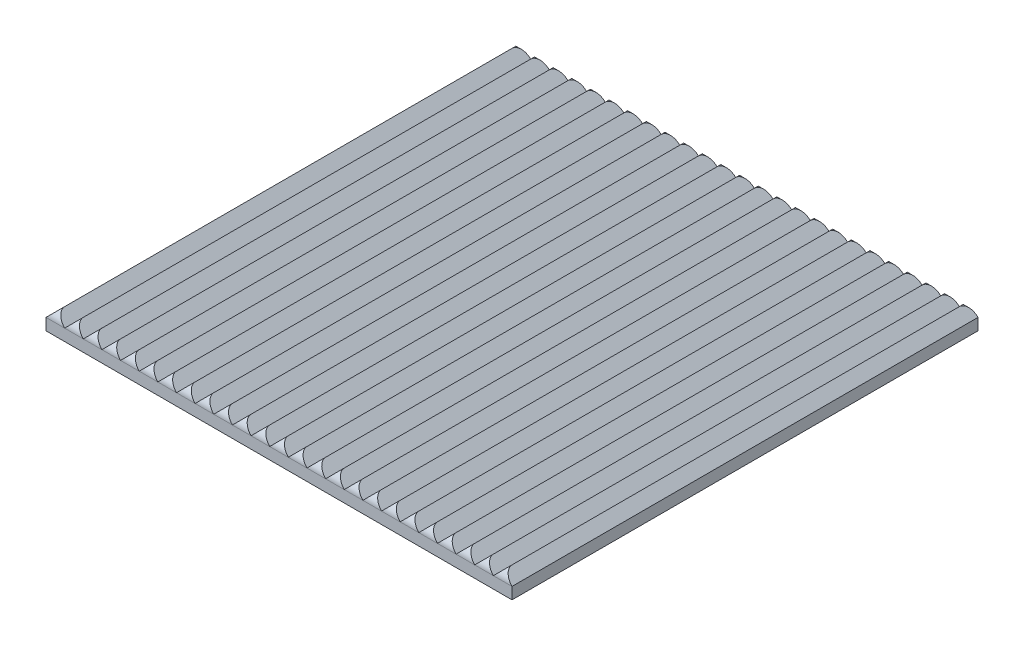
SolidWorks part; units mm, degrees
ref_plane "Front Plane" through (0, 0, 0) normal (0, 0, 1) x (1, 0, 0)
ref_plane "Top Plane" through (0, 0, 0) normal (0, 1, 0) x (1, 0, 0)
ref_plane "Right Plane" through (0, 0, 0) normal (1, 0, 0) x (0, 0, -1)
sketch "Sketch1" plane through (0, 0, 0) normal (0, 1, 0) x (1, 0, 0)
  line L0 (-27.5, 27.5) -> (27.5, 27.5)
  line L1 (-30, -30) -> (30, -30)
  line L2 (-30, -30) -> (-30, 30)
  line L3 (-30, 30) -> (30, 30)
  line L4 (30, -30) -> (30, 30)
  line L5 (-30, -30) -> (30, 30) construction
  line L6 (-30, 30) -> (30, -30) construction
  line L7 (27.5, -27.5) -> (27.5, 27.5)
  line L8 (-27.5, -27.5) -> (27.5, -27.5)
  line L9 (-27.5, -27.5) -> (-27.5, 27.5)
  point P0 (0, 0)
  dimension "D1" = 60
  dimension "D2" = 60
  dimension "D3" = 2.5
extrude "Boss-Extrude1" add sketch "Sketch1" along normal blind 40
sketch "Sketch2" plane through (0, 40, 0) normal (0, 1, 0) x (1, 0, 0)
  line L1 (-30, 30) -> (30, 30)
  line L2 (-30, 30) -> (-30, -30)
  line L3 (-30, -30) -> (30, -30)
  line L4 (30, 30) -> (30, -30)
extrude "Boss-Extrude2" add sketch "Sketch2" along normal blind 2.5
sketch "Sketch3" plane through (0, 0, -30) normal (0, 0, -1) x (-1, 0, 0)
  line L0 (-30, 42.5) -> (-28.8, 43.7)
  line L1 (-28.8, 43.7) -> (-27.6, 42.5)
  line L2 (-30, 42.5) -> (30, 42.5) construction
  line L3 (-27.6, 42.5) -> (-26.4, 43.7)
  line L4 (-26.4, 43.7) -> (-25.2, 42.5)
  line L5 (-25.2, 42.5) -> (-24, 43.7)
  line L6 (-24, 43.7) -> (-22.8, 42.5)
  line L7 (-22.8, 42.5) -> (-21.6, 43.7)
  line L8 (-21.6, 43.7) -> (-20.4, 42.5)
  line L9 (-20.4, 42.5) -> (-19.2, 43.7)
  line L10 (-19.2, 43.7) -> (-18, 42.5)
  line L11 (-18, 42.5) -> (-16.8, 43.7)
  line L12 (-16.8, 43.7) -> (-15.6, 42.5)
  line L13 (-15.6, 42.5) -> (-14.4, 43.7)
  line L14 (-14.4, 43.7) -> (-13.2, 42.5)
  line L15 (-13.2, 42.5) -> (-12, 43.7)
  line L16 (-12, 43.7) -> (-10.8, 42.5)
  line L17 (-10.8, 42.5) -> (-9.6, 43.7)
  line L18 (-9.6, 43.7) -> (-8.4, 42.5)
  line L19 (-8.4, 42.5) -> (-7.2, 43.7)
  line L20 (-7.2, 43.7) -> (-6, 42.5)
  line L21 (-6, 42.5) -> (-4.8, 43.7)
  line L22 (-4.8, 43.7) -> (-3.6, 42.5)
  line L23 (-3.6, 42.5) -> (-2.4, 43.7)
  line L24 (-2.4, 43.7) -> (-1.2, 42.5)
  line L25 (-1.2, 42.5) -> (0, 43.7)
  line L26 (0, 43.7) -> (1.2, 42.5)
  line L27 (1.2, 42.5) -> (2.4, 43.7)
  line L28 (2.4, 43.7) -> (3.6, 42.5)
  line L29 (3.6, 42.5) -> (4.8, 43.7)
  line L30 (4.8, 43.7) -> (6, 42.5)
  line L31 (6, 42.5) -> (7.2, 43.7)
  line L32 (7.2, 43.7) -> (8.4, 42.5)
  line L33 (8.4, 42.5) -> (9.6, 43.7)
  line L34 (9.6, 43.7) -> (10.8, 42.5)
  line L35 (10.8, 42.5) -> (12, 43.7)
  line L36 (12, 43.7) -> (13.2, 42.5)
  line L37 (13.2, 42.5) -> (14.4, 43.7)
  line L38 (14.4, 43.7) -> (15.6, 42.5)
  line L39 (15.6, 42.5) -> (16.8, 43.7)
  line L40 (16.8, 43.7) -> (18, 42.5)
  line L41 (18, 42.5) -> (19.2, 43.7)
  line L42 (19.2, 43.7) -> (20.4, 42.5)
  line L43 (20.4, 42.5) -> (21.6, 43.7)
  line L44 (21.6, 43.7) -> (22.8, 42.5)
  line L45 (22.8, 42.5) -> (24, 43.7)
  line L46 (24, 43.7) -> (25.2, 42.5)
  line L47 (25.2, 42.5) -> (26.4, 43.7)
  line L48 (26.4, 43.7) -> (27.6, 42.5)
  line L49 (27.6, 42.5) -> (28.8, 43.7)
  line L50 (28.8, 43.7) -> (30, 42.5)
  line L51 (-30, 42.5) -> (-30, 42.1701)
  line L52 (-30, 42.5) -> (-30, 0) construction
  line L53 (-30, 42.1701) -> (30, 42.1701)
  line L54 (30, 42.5) -> (30, 0) construction
  line L55 (30, 42.1701) -> (30, 42.5)
  dimension "D1" = 2.4
  dimension "D2" = 1.6971
  dimension "D3" = 25
extrude "Boss-Extrude3" add sketch "Sketch3" against normal up to surface (60 mm away) contours L46 L47 L48 L49 L50 L55 L53 L51 L0 L1 L3 L4 L5 L6 L7 L8 L9 L10 L11 L12 L13 L14 L15 L16 L17 L18 L19 L20 L21 L22 L23 L24 L25 L26 L27 L28 L29 L30 L31 L32 L33 L34 L35 L36 L37 L38 L39 L40 L41 L42 L43 L44 L45 up to face at (0, 21.25, 30)
sketch "Sketch4" plane through (-30, 0, 0) normal (-1, 0, 0) x (0, 0, 1)
  line L0 (-28.8, 42.5) -> (-28.8, 43.7) construction
  line L1 (-28.8, 43.7) -> (-28.8, 42.5) construction
  line L2 (-28.8, 42.5) -> (-30, 42.5) construction
  line L3 (-30, 42.5) -> (-30, 0) construction
  line L4 (30, 43.7) -> (-30, 43.7) construction
  line L5 (-30, 42.5) -> (-30, 43.7)
  line L6 (-30, 43.7) -> (-28.8, 43.7)
  arc A0 (-28.8, 43.7) -> (-30, 42.5) centre (-28.8, 42.5) ccw
  dimension "D1" = 1.2
extrude "Cut-Extrude1" cut sketch "Sketch4" against normal up to surface (60 mm away) up to face at (30, 21.25, 0)
mirror "Mirror1" about plane through (0, 0, 0) normal (0, 0, 1) of "Cut-Extrude1"
sketch "Sketch5" plane through (0, 0, 30) normal (0, 0, 1) x (1, 0, 0)
  line L0 (33, 0) -> (-33, 0) construction
  line L1 (30, 0) -> (-30, 0)
  line L2 (30, 0) -> (30, 41)
  line L3 (30, 41) -> (-30, 41)
  line L4 (-30, 0) -> (-30, 41)
  line L5 (30, 42.5) -> (30, 0) construction
  line L6 (-30, 42.5) -> (-30, 0) construction
  line L7 (-27.6, 42.5) -> (-30, 42.5) construction
  dimension "D1" = 1.5
extrude "Cut-Extrude2" cut sketch "Sketch5" against normal through all both and the other way through all
